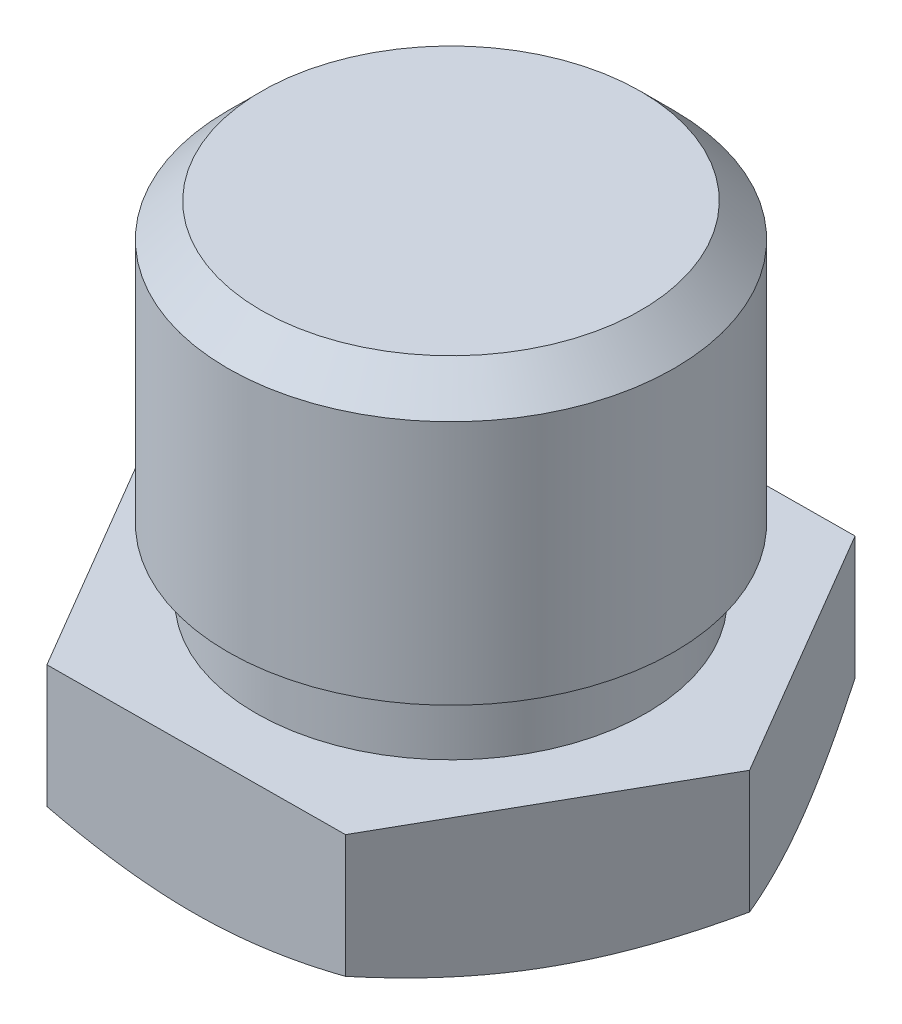
SolidWorks part; units mm, degrees
ref_plane "前视基准面" through (0, 0, 0) normal (0, 0, 1) x (1, 0, 0)
ref_plane "上视基准面" through (0, 0, 0) normal (0, 1, 0) x (1, 0, 0)
ref_plane "右视基准面" through (0, 0, 0) normal (1, 0, 0) x (0, 0, -1)
sketch "草图1" plane through (0, 0, 0) normal (0, 1, 0) x (1, 0, 0)
  line L1 (6.5533, 11.5494) -> (-6.7254, 11.45)
  line L2 (-6.7254, 11.45) -> (-13.2787, -0.0994)
  line L3 (-13.2787, -0.0994) -> (-6.5533, -11.5494)
  line L4 (-6.5533, -11.5494) -> (6.7254, -11.45)
  line L5 (6.7254, -11.45) -> (13.2787, 0.0994)
  line L6 (13.2787, 0.0994) -> (6.5533, 11.5494)
  circle A0 centre (0, 0) radius 11.5 construction
  dimension "D1" = 23
extrude "凸台-拉伸1" add sketch "草图1" along normal blind 6.5
sketch "草图2" plane through (0, 6.5, 0) normal (0, 1, 0) x (1, 0, 0)
  circle A0 centre (0, 0) radius 8.75
extrude "凸台-拉伸2" add sketch "草图2" along normal blind 3
sketch "草图3" plane through (0, 9.5, 0) normal (0, 1, 0) x (1, 0, 0)
  circle A0 centre (0, 0) radius 10
  dimension "D1" = 20
extrude "凸台-拉伸3" add sketch "草图3" along normal blind 12.5 contours A0
chamfer "倒角1" distance 1.5 angle 45 1 edges at (0, 22, 10)
ref_plane "基准面1" through (0, 0, 0) normal (0.8697, 0, 0.4935) x (0.4935, 0, -0.8697)
sketch "草图5" plane through (0, 0, 0) normal (0.8697, 0, 0.4935) x (0.4935, 0, -0.8697)
  line L0 (13.2791, 1) -> (11.2791, 0)
  line L1 (13.2791, 6.5) -> (13.2791, 0) construction
  line L2 (6.6395, 0) -> (13.2791, 0) construction
  line L3 (11.2791, 0) -> (13.2791, 0)
  line L4 (13.2791, 0) -> (13.2791, 1)
  line L5 (0, -1000) -> (0, 49000) construction
  dimension "D1" = 1
  dimension "D2" = 2
revolve "切除-旋转3" cut sketch "草图5" angle 360 about L5
